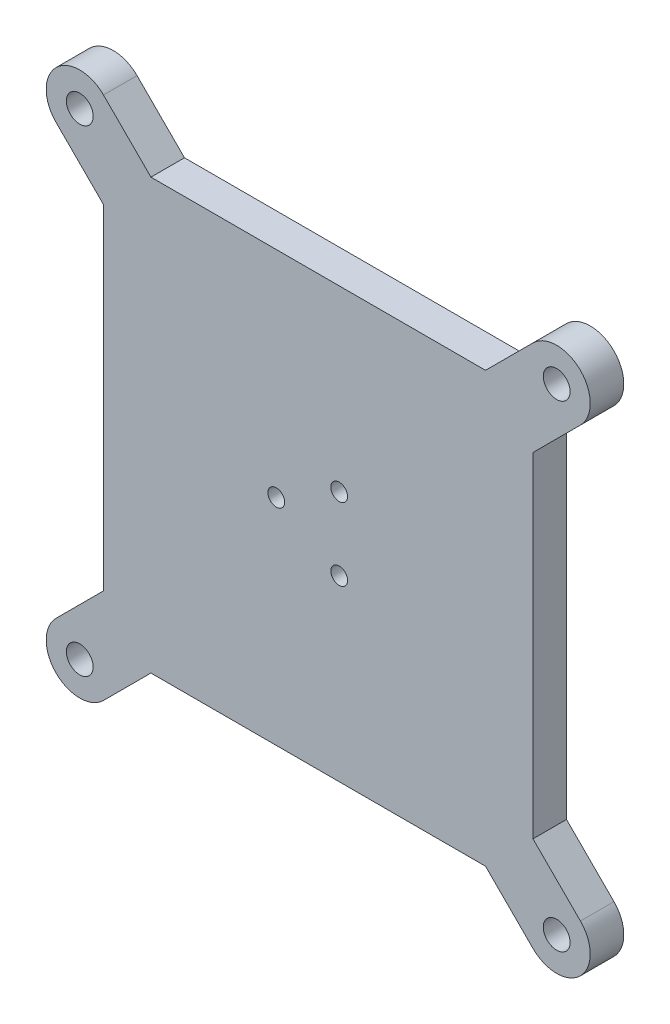
SolidWorks part; units mm, degrees
ref_plane "Front Plane" through (0, 0, 0) normal (0, 0, 1) x (1, 0, 0)
ref_plane "Top Plane" through (0, 0, 0) normal (0, 1, 0) x (1, 0, 0)
ref_plane "Right Plane" through (0, 0, 0) normal (1, 0, 0) x (0, 0, -1)
sketch "Sketch1" plane through (0, 0, 0) normal (0, 0, 1) x (1, 0, 0)
  line L0 (3.125, 5.4127) -> (3.125, -5.4127) construction
  line L1 (3.125, -5.4127) -> (-6.25, 0) construction
  line L2 (-6.25, 0) -> (3.125, 5.4127) construction
  line L3 (0, 0) -> (-6.25, 0) construction
  line L20 (-44, 9) -> (-44, -9)
  line L21 (-44, -9) -> (-35, -9)
  line L22 (-32, -12) -> (-32, -24.9289)
  line L23 (-32, -24.9289) -> (-39.0711, -32)
  line L24 (-32, -39.0711) -> (-24.9289, -32)
  line L25 (-24.9289, -32) -> (24.9289, -32)
  line L26 (24.9289, -32) -> (32, -39.0711)
  line L27 (39.0711, -32) -> (32, -24.9289)
  line L28 (32, -24.9289) -> (32, 24.9289)
  line L29 (32, 24.9289) -> (39.0711, 32)
  line L30 (32, 39.0711) -> (24.9289, 32)
  line L31 (24.9289, 32) -> (12, 32)
  line L32 (9, 35) -> (9, 44)
  line L33 (9, 44) -> (-9, 44)
  line L34 (-9, 44) -> (-9, 35)
  line L35 (-12, 32) -> (-24.9289, 32)
  line L36 (-24.9289, 32) -> (-32, 39.0711)
  line L37 (-39.0711, 32) -> (-32, 24.9289)
  line L38 (-32, 24.9289) -> (-32, 12)
  line L39 (-35, 9) -> (-44, 9)
  line L43 (-32, -24.9289) -> (-39.0711, -32)
  line L44 (-32, -39.0711) -> (-24.9289, -32)
  line L45 (-24.9289, -32) -> (24.9289, -32)
  line L46 (24.9289, -32) -> (32, -39.0711)
  line L47 (39.0711, -32) -> (32, -24.9289)
  line L48 (32, -24.9289) -> (32, 24.9289)
  line L49 (32, 24.9289) -> (39.0711, 32)
  line L50 (32, 39.0711) -> (24.9289, 32)
  line L55 (24.9289, 32) -> (-24.9289, 32)
  line L56 (-24.9289, 32) -> (-32, 39.0711)
  line L57 (-39.0711, 32) -> (-32, 24.9289)
  line L58 (-32, 24.9289) -> (-32, -24.9289)
  circle A1 centre (0, 0) radius 6.25 construction
  circle A2 centre (3.125, -5.4127) radius 1.25
  circle A3 centre (-6.25, 0) radius 1.25
  circle A4 centre (3.125, 5.4127) radius 1.25
  circle A5 centre (-35.5355, -35.5355) radius 2 construction
  circle A6 centre (35.5355, -35.5355) radius 2 construction
  circle A7 centre (35.5355, 35.5355) radius 2 construction
  arc A8 (-32, -12) -> (-35, -9) centre (-35, -12) ccw
  arc A9 (-39.0711, -32) -> (-32, -39.0711) centre (-35.5355, -35.5355) ccw
  arc A10 (32, -39.0711) -> (39.0711, -32) centre (35.5355, -35.5355) ccw
  arc A11 (39.0711, 32) -> (32, 39.0711) centre (35.5355, 35.5355) ccw
  arc A12 (9, 35) -> (12, 32) centre (12, 35) ccw
  arc A13 (-12, 32) -> (-9, 35) centre (-12, 35) ccw
  arc A14 (-32, 39.0711) -> (-39.0711, 32) centre (-35.5355, 35.5355) ccw
  arc A15 (-35, 9) -> (-32, 12) centre (-35, 12) ccw
  arc A17 (-39.0711, -32) -> (-32, -39.0711) centre (-35.5355, -35.5355) ccw
  arc A18 (32, -39.0711) -> (39.0711, -32) centre (35.5355, -35.5355) ccw
  arc A19 (39.0711, 32) -> (32, 39.0711) centre (35.5355, 35.5355) ccw
  arc A22 (-32, 39.0711) -> (-39.0711, 32) centre (-35.5355, 35.5355) ccw
  circle A24 centre (-35.5355, 35.5355) radius 2 construction
  circle A25 centre (-35.5355, -35.5355) radius 2
  circle A26 centre (35.5355, -35.5355) radius 2
  circle A27 centre (35.5355, 35.5355) radius 2
  circle A28 centre (-35.5355, 35.5355) radius 2
  point P53 (-6.25, 0)
  dimension "D2" = 12.5
  dimension "2" = 2.5
  dimension "D1" = 0
extrude "Boss-Extrude1" add sketch "Sketch1" along normal blind 5
sketch "Sketch2" plane through (0, 0, 0) normal (0, 0, -1) x (-1, 0, 0)
  circle A0 centre (-3.125, 5.4127) radius 1.25 construction
  circle A1 centre (-3.125, -5.4127) radius 1.25 construction
  circle A2 centre (6.25, 0) radius 1.25 construction
  circle A3 centre (-3.125, 5.4127) radius 1.25 construction
  circle A4 centre (-3.125, -5.4127) radius 1.25 construction
  circle A5 centre (6.25, 0) radius 1.25 construction
  circle A6 centre (-3.125, 5.4127) radius 2.25
  circle A7 centre (-3.125, -5.4127) radius 2.25
  circle A8 centre (6.25, 0) radius 2.25
  dimension "D1" = 1
extrude "Cut-Extrude1" cut sketch "Sketch2" against normal blind 1.5
